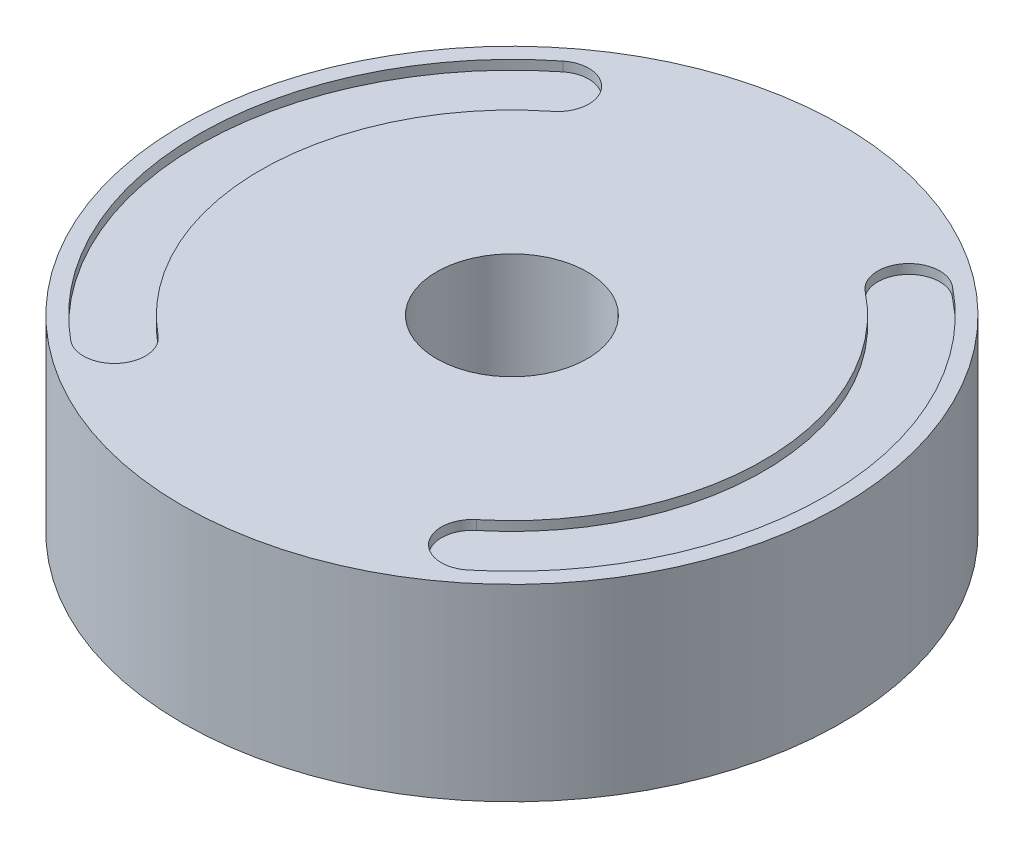
SolidWorks part; units mm, degrees
ref_plane "前视基准面" through (0, 0, 0) normal (0, 0, 1) x (1, 0, 0)
ref_plane "上视基准面" through (0, 0, 0) normal (0, 1, 0) x (1, 0, 0)
ref_plane "右视基准面" through (0, 0, 0) normal (1, 0, 0) x (0, 0, -1)
sketch "草图3" plane through (0, 0, 0) normal (0, 1, 0) x (1, 0, 0)
  circle A0 centre (-175, 0) radius 17.5
  circle A1 centre (-175, 0) radius 4
  circle A2 centre (-175, 0) radius 4 construction
  dimension "D1" = 35
extrude "凸台-拉伸1" add sketch "草图3" along normal blind 10
sketch "草图5" plane through (0, 10, 0) normal (0, 1, 0) x (1, 0, 0)
  line L0 (-175, 0) -> (-175, 19.0269) construction
  arc A0 (-165.4954, -11.6044) -> (-165.6807, 11.7538) centre (-175, 0) ccw construction
  arc A1 (-164.4515, -12.879) -> (-164.6572, 13.0447) centre (-175, 0) ccw
  arc A2 (-166.5393, -10.3299) -> (-166.7043, 10.4628) centre (-175, 0) ccw
  arc A3 (-166.5393, -10.3299) -> (-164.4515, -12.879) centre (-165.4954, -11.6044) ccw
  arc A4 (-164.6572, 13.0447) -> (-166.7043, 10.4628) centre (-165.6807, 11.7538) ccw
  arc A5 (-184.5046, -11.6044) -> (-184.3193, 11.7538) centre (-175, 0) cw construction
  arc A6 (-185.5485, -12.879) -> (-185.3428, 13.0447) centre (-175, 0) cw
  arc A7 (-183.4607, -10.3299) -> (-183.2957, 10.4628) centre (-175, 0) cw
  arc A8 (-183.4607, -10.3299) -> (-185.5485, -12.879) centre (-184.5046, -11.6044) cw
  arc A9 (-185.3428, 13.0447) -> (-183.2957, 10.4628) centre (-184.3193, 11.7538) cw
  point P4 (-160.0005, 0.119)
  point P13 (-189.9995, 0.119)
  dimension "D1" = 15
extrude "切除-拉伸1" cut sketch "草图5" against normal blind 0.5
